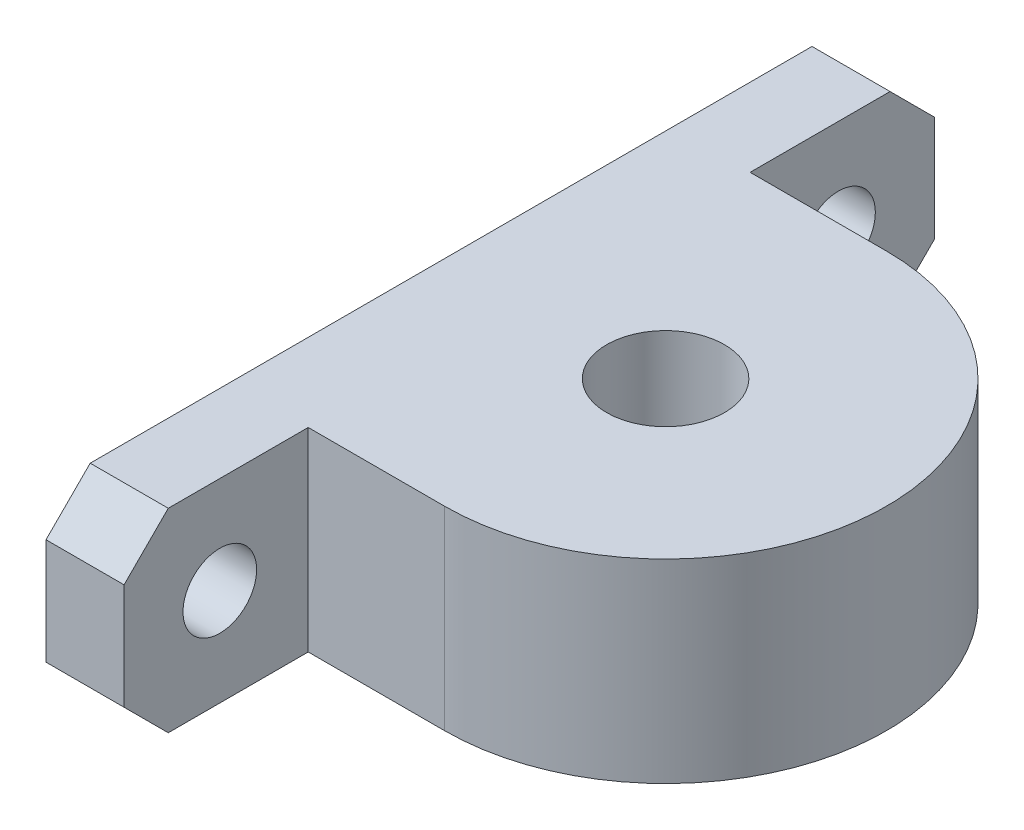
SolidWorks part; units mm, degrees
ref_plane "Front Plane" through (0, 0, 0) normal (0, 0, 1) x (1, 0, 0)
ref_plane "Top Plane" through (0, 0, 0) normal (0, 1, 0) x (1, 0, 0)
ref_plane "Right Plane" through (0, 0, 0) normal (1, 0, 0) x (0, 0, -1)
sketch "Sketch2" plane through (0, 0, 0) normal (0, 1, 0) x (1, 0, 0)
  line L2 (-14.56, -27.5) -> (-9.26, -27.5)
  line L3 (-9.26, -27.5) -> (-9.26, -15)
  line L5 (0, 15) -> (-9.26, 15)
  line L7 (-9.26, 27.5) -> (-9.26, 15)
  line L8 (-14.56, 27.5) -> (-9.26, 27.5)
  line L9 (-14.56, -27.5) -> (-14.56, 27.5)
  line L11 (0, -15) -> (-9.26, -15)
  circle A0 centre (0, 0) radius 4
  arc A2 (0, -15) -> (0, 15) centre (0, 0) ccw
  point P3 (15, 0)
  point P7 (-14.56, 0)
  dimension "D1" = 8
  dimension "D2" = 55
  dimension "D3" = 15
  dimension "D4" = 5.3
  dimension "D5" = 29.56
extrude "Boss-Extrude2" add sketch "Sketch2" along normal blind 13.2
hole_wizard "Ø5.0 (5) Diameter Hole1" positions "Sketch3" profile "Sketch4" hole size "Ø5.0" standard "ANSI Metric" end condition through all
sketch "Sketch3" plane through (-9.26, 0, 0) normal (1, 0, 0) x (0, 0, -1)
  line L4 (21, 6.6) -> (-21, 6.6) construction
  line L8 (0, 0) -> (0, 13.2) construction
  line L9 (15, 13.2) -> (-15, 13.2) construction
  point P0 (21, 6.6)
  point P20 (-21, 6.6)
  point P36 (0, 6.6)
  dimension "D1" = 42
sketch "Sketch4" plane through (-9.26, 6.6, -21) normal (0, 1, 0) x (0, 0, -1)
  line L0 (0, 0) -> (0, 5.3)
  line L1 (0, 5.3) -> (2.5, 5.3)
  line L2 (2.5, 5.3) -> (2.5, 0)
  line L5 (2.5, 0) -> (0, 0)
  line L11 (0, -6.35) -> (0, 107.95) construction
  dimension "Thru Hole Dia." = 5
  dimension "Thru Hole Depth" = 5.3
chamfer "Chamfer1" distance 3 angle 45 4 edges at (-11.91, 13.2, -27.5) (-11.91, 0, -27.5) (-11.91, 13.2, 27.5) (-11.91, 0, 27.5)
sketch "Sketch5" plane through (-14.56, 0, 0) normal (-1, 0, 0) x (0, 0, 1)
  line L8 (24.5, 13.2) -> (-24.5, 13.2)
  line L9 (-24.5, 13.2) -> (-27.5, 10.2)
  line L10 (-27.5, 10.2) -> (-27.5, 3)
  line L11 (-27.5, 3) -> (-24.5, 0)
  line L12 (-24.5, 0) -> (24.5, 0)
  line L13 (24.5, 0) -> (27.5, 3)
  line L14 (27.5, 3) -> (27.5, 10.2)
  line L15 (27.5, 10.2) -> (24.5, 13.2)
  line L16 (24.5, 13.2) -> (-24.5, 13.2)
  line L17 (-24.5, 13.2) -> (-27.5, 10.2)
  line L18 (-27.5, 10.2) -> (-27.5, 3)
  line L19 (-27.5, 3) -> (-24.5, 0)
  line L20 (-24.5, 0) -> (24.5, 0)
  line L21 (24.5, 0) -> (27.5, 3)
  line L22 (27.5, 3) -> (27.5, 10.2)
  line L23 (27.5, 10.2) -> (24.5, 13.2)
  circle A0 centre (21, 6.6) radius 2.5 construction
  circle A1 centre (-21, 6.6) radius 2.5 construction
  circle A2 centre (21, 6.6) radius 2.5
  circle A3 centre (-21, 6.6) radius 2.5
  dimension "D1" = 0
